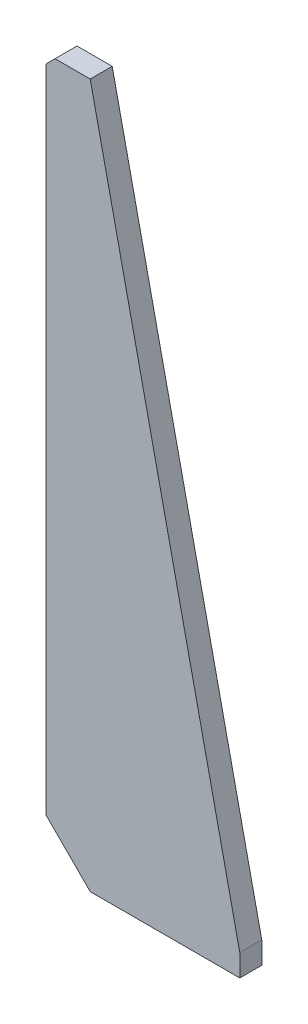
SolidWorks part; units mm, degrees
material "AISI 304"
ref_plane "Спереди" through (0, 0, 0) normal (0, 0, 1) x (1, 0, 0)
ref_plane "Сверху" through (0, 0, 0) normal (0, 1, 0) x (1, 0, 0)
ref_plane "Справа" through (0, 0, 0) normal (1, 0, 0) x (0, 0, -1)
other "Configuration Table"
sketch "Эскиз1" plane through (0, 0, 0) normal (0, 0, 1) x (1, 0, 0)
  line L0 (0, 0) -> (0, 160)
  line L1 (0, 160) -> (10, 160)
  line L2 (10, 160) -> (44, 5)
  line L3 (44, 5) -> (44, 0)
  line L4 (44, 0) -> (0, 0)
  dimension "D1" = 44
  dimension "D2" = 160
  dimension "D3" = 5
  dimension "D4" = 10
extrude "Бобышка-Вытянуть1" add sketch "Эскиз1" along normal mid plane 5
chamfer "Фаска1" distance 10 angle 45 1 edges at (0, 0, 0)
chamfer "Фаска2" distance 2 angle 45 1 edges at (0, 160, 0)
move or copy body "Тело-Переместить/Копировать2" [suppressed] bodies to move or copy 103 parameters "D1"=0, "D2"=0, "D3"=0
move or copy body "Тело-Переместить/Копировать3" [suppressed] bodies to move or copy 105 parameters "D1"=0, "D2"=0, "D3"=0
move or copy body "Тело-Переместить/Копировать4" [suppressed] bodies to move or copy 106 parameters "D1"=0, "D2"=0, "D3"=0
move or copy body "Тело-Переместить/Копировать5" [suppressed] bodies to move or copy 107 parameters "D1"=0, "D2"=0, "D3"=0
move or copy body "Тело-Переместить/Копировать1" [suppressed] bodies to move or copy 103 parameters "D1"=0, "D2"=0, "D3"=0
